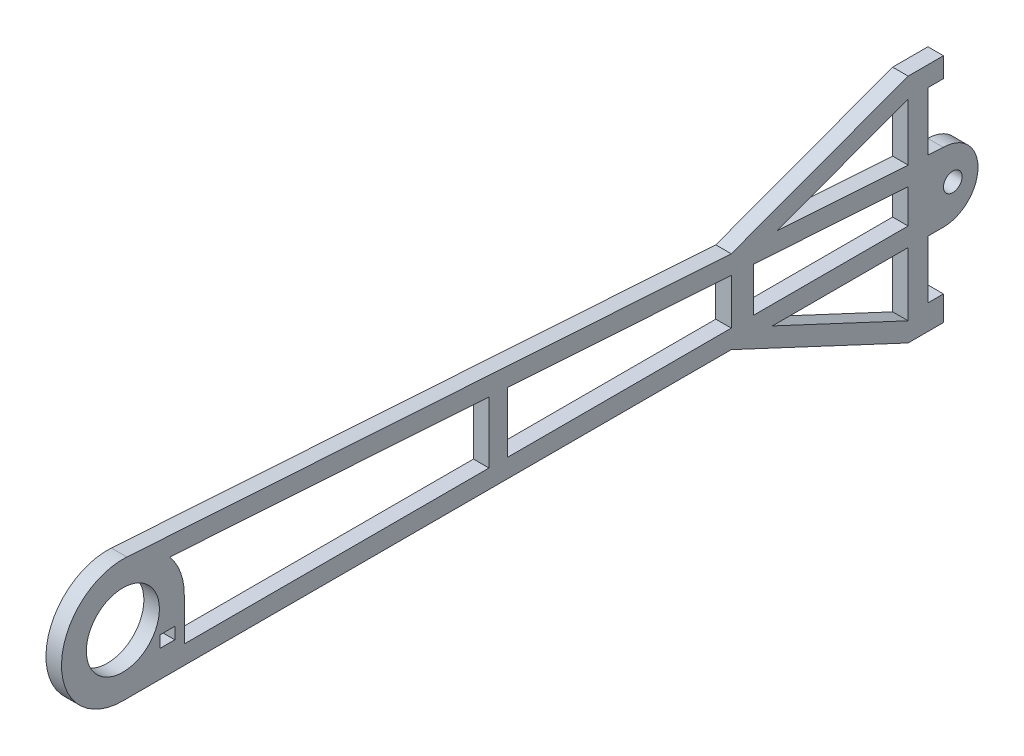
SolidWorks part; units mm, degrees
material "Delrin"
ref_plane "Front Plane" through (0, 0, 0) normal (0, 0, 1) x (1, 0, 0)
ref_plane "Top Plane" through (0, 0, 0) normal (0, 1, 0) x (1, 0, 0)
ref_plane "Right Plane" through (0, 0, 0) normal (1, 0, 0) x (0, 0, -1)
sketch "Sketch1" plane through (0, 0, 0) normal (1, 0, 0) x (0, 0, -1)
  line L0 (0.4103, 6.2604) -> (62.1851, 2.2118)
  line L1 (0, -6.2738) -> (62.1851, -6.2738)
  line L2 (80.264, 8.901) -> (83.8708, 8.901)
  line L3 (4.7788, 4.065) -> (80.264, -0.8821)
  line L4 (4.5027, -4.3688) -> (80.264, -4.3688)
  line L5 (-0.9662, 4.4415) -> (82.6296, -1.0372) construction
  line L6 (0, -4.3688) -> (80.264, -4.3688) construction
  line L7 (80.264, -6.2738) -> (80.264, 8.901) construction
  line L8 (5.3467, -3.556) -> (5.3467, -2.286) construction
  line L9 (5.3467, -2.286) -> (3.7592, -2.286) construction
  line L10 (3.7592, -3.556) -> (3.7592, -2.286) construction
  line L11 (5.3467, -3.556) -> (3.7592, -3.556) construction
  line L12 (5.3467, -3.556) -> (5.3467, -2.286) construction
  line L13 (5.3467, -2.286) -> (3.7592, -2.286) construction
  line L14 (3.7592, -3.556) -> (3.7592, -2.286) construction
  line L15 (5.3467, -3.556) -> (3.7592, -3.556) construction
  line L16 (6.2738, 0) -> (6.2738, -4.3688)
  line L17 (39.3251, 1.8009) -> (39.3251, -4.3688)
  line L18 (37.4201, 1.9258) -> (37.4201, -4.3688)
  line L19 (5.3086, -2.3241) -> (3.7973, -2.3241)
  line L20 (3.7973, -3.5179) -> (3.7973, -2.3241)
  line L21 (5.3086, -3.5179) -> (3.7973, -3.5179)
  line L22 (5.3086, -3.5179) -> (5.3086, -2.3241)
  line L23 (-0.8416, 6.3424) -> (82.7541, 0.8638) construction
  line L24 (83.8708, 6.869) -> (83.8708, 8.901)
  line L25 (83.8708, -12.181) -> (83.8708, -14.721)
  line L26 (83.8708, 6.869) -> (82.296, 6.869)
  line L27 (82.296, 6.869) -> (82.296, -12.181)
  line L28 (82.296, -12.181) -> (83.8708, -12.181)
  line L29 (83.8708, 6.869) -> (83.8708, -12.181) construction
  line L32 (83.8708, -14.721) -> (80.264, -14.721)
  line L33 (80.264, -14.721) -> (80.264, -6.2738) construction
  line L36 (64.4711, 0.1529) -> (64.4711, -4.3688)
  line L37 (62.1851, 0.3027) -> (62.1851, -4.3688)
  line L38 (62.1851, 2.2118) -> (80.264, 8.901)
  line L39 (66.8488, 1.9062) -> (80.264, 6.8697)
  line L40 (62.1851, -6.2738) -> (80.264, -14.721)
  line L41 (66.3853, -6.2738) -> (80.264, -12.7585)
  line L42 (62.9378, -4.663) -> (81.0167, -13.1102) construction
  line L43 (62.8461, 0.4252) -> (80.925, 7.1143) construction
  line L44 (66.3853, -6.2738) -> (83.8708, -6.2738)
  line L45 (0, -6.2738) -> (80.264, -6.2738) construction
  line L46 (66.8488, 1.9062) -> (83.8708, 0.7906)
  line L47 (62.1851, -4.3688) -> (62.1851, 49995.6312) construction
  line L48 (80.264, 6.8697) -> (80.264, 1.027)
  line L49 (80.264, -0.8821) -> (80.264, -4.3688)
  line L50 (80.264, -6.2738) -> (80.264, -12.7585)
  circle A0 centre (0, 0) radius 3.7338
  circle A1 centre (0, 0) radius 6.2738
  arc A2 (83.8708, -6.2738) -> (83.8708, 0.7906) centre (83.8708, -2.7416) ccw
  circle A3 centre (84.8233, -2.7416) radius 0.9525
  dimension "D1" = 7.4676
  dimension "D2" = 2.54
  dimension "D3" = 5.842
  dimension "D8" = 1.5748
  dimension "D21" = 22.86
  dimension "D14" = 1.905
  dimension "D5" = 37.4201
  dimension "D10" = 2.54
  dimension "D11" = 2.032
  dimension "D12" = 1.905
  dimension "D4" = 5.3842
  dimension "D9" = 1.5748
  dimension "D22" = 19.05
  dimension "D23" = 80.264
  dimension "D24" = 2.032
  dimension "D25" = 2.286
  dimension "D6" = 1.905
  dimension "D7" = 1.905
  dimension "D13" = 0.0381
  dimension "D27" = 1.778
  dimension "D28" = 1.905
extrude "Boss-Extrude1" add sketch "Sketch1" along normal blind 1.5875
sketch "Sketch2" plane through (0, 0, -82.296) normal (0, 0, -1) x (-1, 0, 0)
  line L0 (-1.5875, 8.901) -> (0, 8.901) construction
  line L1 (-1.5875, 6.869) -> (0, 6.869) construction
  line L2 (-1.5875, -12.181) -> (0, -12.181) construction
  line L3 (-1.5875, -14.721) -> (0, -14.721) construction
  line L4 (-1.5875, 8.901) -> (0, 8.901)
  line L5 (-1.5875, 6.869) -> (0, 6.869)
  line L6 (-1.5875, -12.181) -> (0, -12.181)
  line L7 (-1.5875, -14.721) -> (0, -14.721)
  line L8 (-1.5875, 8.901) -> (-1.5875, 6.869)
  line L9 (0, 8.901) -> (0, 6.869)
  line L10 (-1.5875, -12.181) -> (-1.5875, -14.721)
  line L11 (0, -12.181) -> (0, -14.721)
